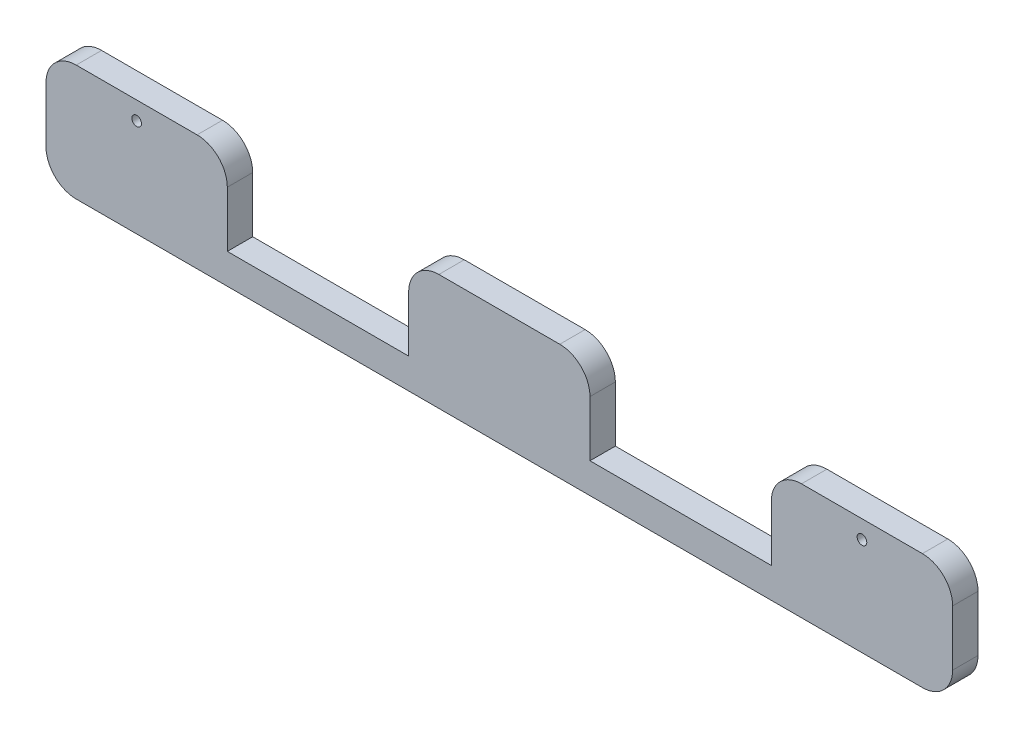
SolidWorks part; units mm, degrees
ref_plane "Front Plane" through (0, 0, 0) normal (0, 0, 1) x (1, 0, 0)
ref_plane "Top Plane" through (0, 0, 0) normal (0, 1, 0) x (1, 0, 0)
ref_plane "Right Plane" through (0, 0, 0) normal (1, 0, 0) x (0, 0, -1)
sketch "Sketch1" plane through (0, 0, 0) normal (0, 0, 1) x (1, 0, 0)
  line L1 (-85.0624, -35.0708) -> (105.4376, -35.0708)
  line L2 (-85.0624, -35.0708) -> (-85.0624, -59.4548)
  line L3 (-85.0624, -59.4548) -> (105.4376, -59.4548)
  line L4 (105.4376, -35.0708) -> (105.4376, -59.4548)
  dimension "D1" = 190.5
  dimension "D2" = 24.384
extrude "Boss-Extrude1" add sketch "Sketch1" along normal blind 5.334
sketch "Sketch3" plane through (0, 0, 5.334) normal (0, 0, 1) x (1, 0, 0)
  line L0 (105.4376, -35.0708) -> (-85.0624, -35.0708) construction
  line L1 (-46.9624, -35.0708) -> (-8.8624, -35.0708)
  line L2 (-46.9624, -35.0708) -> (-46.9624, -53.1048)
  line L3 (-46.9624, -53.1048) -> (-8.8624, -53.1048)
  line L4 (-8.8624, -35.0708) -> (-8.8624, -53.1048)
  line L5 (-8.8624, -53.1048) -> (29.2376, -53.1048) construction
  line L6 (29.2376, -35.0708) -> (67.3376, -35.0708)
  line L7 (29.2376, -35.0708) -> (29.2376, -53.1048)
  line L8 (29.2376, -53.1048) -> (67.3376, -53.1048)
  line L9 (67.3376, -35.0708) -> (67.3376, -53.1048)
  line L10 (67.3376, -53.1048) -> (105.4376, -53.1048) construction
  line L11 (105.4376, -59.4548) -> (105.4376, -35.0708) construction
  line L12 (-46.9624, -53.1048) -> (-85.0624, -53.1048) construction
  line L13 (-85.0624, -35.0708) -> (-85.0624, -59.4548) construction
  dimension "D1" = 18.034
extrude "Cut-Extrude1" cut sketch "Sketch3" against normal through all
sketch "Sketch4" plane through (0, 0, 5.334) normal (0, 0, 1) x (1, 0, 0)
  line L0 (-46.9624, -35.0708) -> (-85.0624, -35.0708) construction
  line L1 (-46.9624, -35.0708) -> (-46.9624, -53.1048) construction
  line L2 (10.1876, -35.0708) -> (10.1876, -59.4548) construction
  line L3 (29.2376, -35.0708) -> (-8.8624, -35.0708) construction
  line L4 (-85.0624, -59.4548) -> (105.4376, -59.4548) construction
  circle A0 centre (-66.0124, -38.8808) radius 1.016
  circle A1 centre (86.3876, -38.8808) radius 1.016
  dimension "D1" = 2.032
  dimension "D2" = 3.81
  dimension "D3" = 19.05
extrude "Cut-Extrude2" cut sketch "Sketch4" against normal through all
fillet "Fillet1" radius 6.35 8 edges at (29.2376, -35.0708, 2.667) (-8.8624, -35.0708, 2.667) (-46.9624, -35.0708, 2.667) (67.3376, -35.0708, 2.667) (105.4376, -35.0708, 2.667) (105.4376, -59.4548, 2.667) (-85.0624, -59.4548, 2.667) (-85.0624, -35.0708, 2.667)
equation "\"MDF\"= .21in"
equation "\"Foamcore\"= .13in"
equation "\"Gmaterial\"= \"MDF\""
equation "\"D2@Sketch1\"=\"MDF\"+.25+.5"
equation "\"D1@Boss-Extrude1\"=\"MDF\""
equation "\"D1@Sketch3\"=\"MDF\"+0.5"
